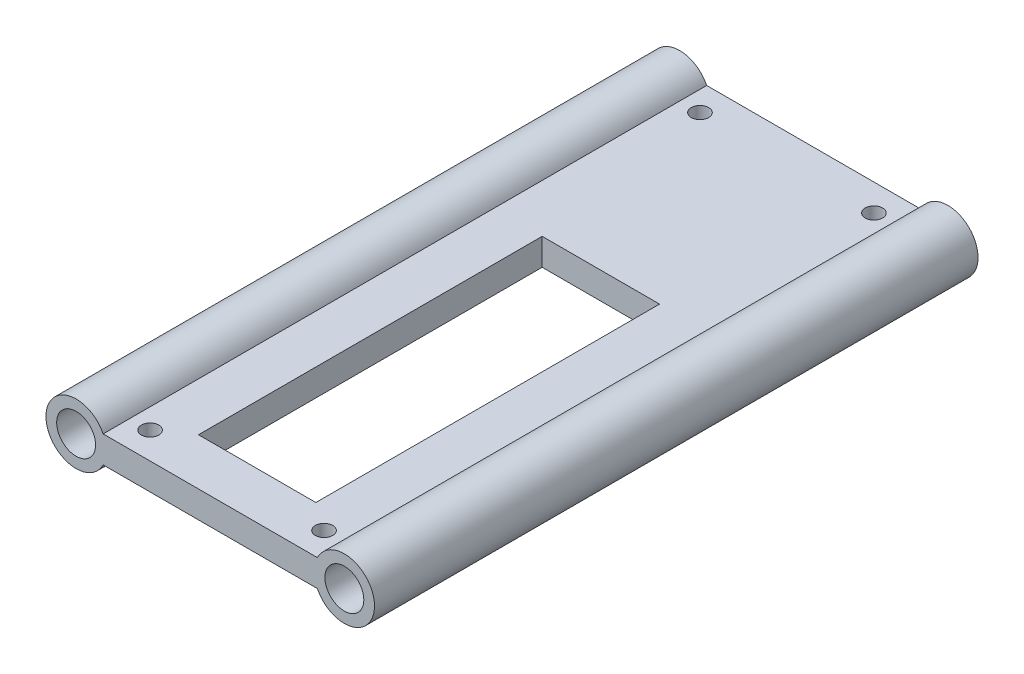
SolidWorks part; units mm, degrees
ref_plane "Front Plane" through (0, 0, 0) normal (0, 0, 1) x (1, 0, 0)
ref_plane "Top Plane" through (0, 0, 0) normal (0, 1, 0) x (1, 0, 0)
ref_plane "Right Plane" through (0, 0, 0) normal (1, 0, 0) x (0, 0, -1)
sketch "Sketch1" plane through (0, 0, 0) normal (0, 0, 1) x (1, 0, 0)
  line L1 (-25.4, -2.54) -> (25.4, -2.54)
  line L2 (-25.4, -2.54) -> (-25.4, 2.54)
  line L3 (-25.4, 2.54) -> (25.4, 2.54)
  line L4 (25.4, -2.54) -> (25.4, 2.54)
  line L5 (-25.4, -2.54) -> (25.4, 2.54) construction
  line L6 (-25.4, 2.54) -> (25.4, -2.54) construction
  circle A0 centre (25.4, 0) radius 3.683
  circle A1 centre (-25.4, 0) radius 3.683
  circle A2 centre (-25.4, 0) radius 5.715
  circle A3 centre (25.4, 0) radius 5.715
  point P4 (0, 0)
  dimension "D1" = 7.366
  dimension "D6" = 11.43
  dimension "D2" = 25.4
  dimension "D3" = 25.4
  dimension "D4" = 5.08
  dimension "D5" = 50.8
extrude "Boss-Extrude1" add sketch "Sketch1" against normal blind 114.3 contours L1 A1 L3 L2 | L3 A1 L1 L2 | A3 L3 A2 L1 | L1 A3 L3 A0 | L3 A3 L1 A0
sketch "Sketch2" plane through (0, 2.54, 0) normal (0, 1, 0) x (1, 0, 0)
  line L0 (-20.2805, 114.3) -> (20.2805, 114.3) construction
  line L1 (-20.2805, 114.3) -> (-20.2805, 0) construction
  line L2 (20.2805, 114.3) -> (20.2805, 0) construction
  line L3 (-20.2805, 0) -> (20.2805, 0) construction
  line L5 (-11.1125, 73.9775) -> (11.1125, 73.9775)
  line L6 (-11.1125, 73.9775) -> (-11.1125, 8.89)
  line L7 (-11.1125, 8.89) -> (11.1125, 8.89)
  line L8 (11.1125, 73.9775) -> (11.1125, 8.89)
  line L9 (-11.1125, 73.9775) -> (11.1125, 8.89) construction
  line L10 (-11.1125, 8.89) -> (11.1125, 73.9775) construction
  circle A0 centre (-16.4705, 109.22) radius 1.651
  circle A1 centre (16.4705, 109.22) radius 1.651
  circle A2 centre (-16.4705, 5.08) radius 1.651
  circle A4 centre (16.4705, 5.08) radius 1.651
  point P16 (0, 41.4337)
  dimension "D1" = 3.302
  dimension "D2" = 5.08
  dimension "D3" = 3.81
  dimension "D4" = 5.08
  dimension "D5" = 3.81
  dimension "D6" = 3.81
  dimension "D7" = 5.08
  dimension "D8" = 5.08
  dimension "D9" = 3.81
  dimension "D10" = 22.225
  dimension "D11" = 65.0875
  dimension "D12" = 8.89
extrude "Cut-Extrude1" cut sketch "Sketch2" against normal blind 114.3
